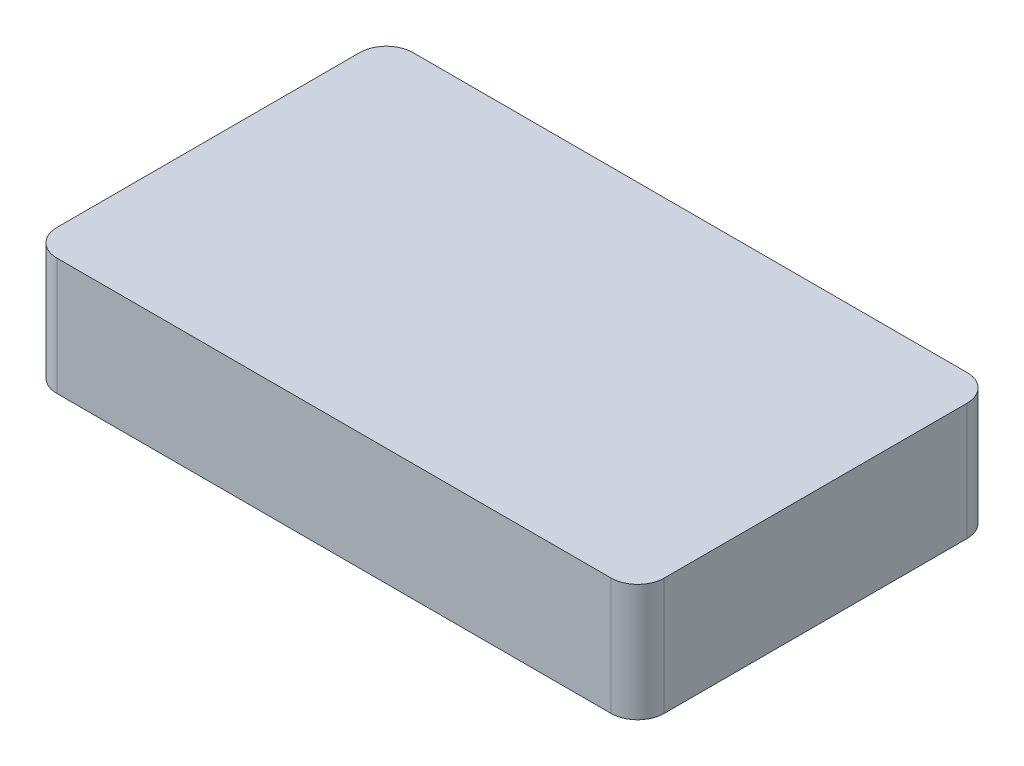
SolidWorks part; units mm, degrees
ref_plane "Front Plane" through (0, 0, 0) normal (0, 0, 1) x (1, 0, 0)
ref_plane "Top Plane" through (0, 0, 0) normal (0, 1, 0) x (1, 0, 0)
ref_plane "Right Plane" through (0, 0, 0) normal (1, 0, 0) x (0, 0, -1)
sketch "Sketch1" plane through (0, 0, 0) normal (0, 1, 0) x (1, 0, 0)
  line L1 (-66.15, 42.5) -> (66.15, 42.5)
  line L2 (-72.5, 36.15) -> (-72.5, -36.15)
  line L3 (-66.15, -42.5) -> (66.15, -42.5)
  line L4 (72.5, 36.15) -> (72.5, -36.15)
  arc A0 (66.15, 42.5) -> (72.5, 36.15) centre (66.15, 36.15) cw
  arc A1 (66.15, -42.5) -> (72.5, -36.15) centre (66.15, -36.15) ccw
  arc A2 (-72.5, -36.15) -> (-66.15, -42.5) centre (-66.15, -36.15) ccw
  arc A3 (-66.15, 42.5) -> (-72.5, 36.15) centre (-66.15, 36.15) ccw
  point P7 (72.5, 42.5)
  point P12 (-72.5, -42.5)
  point P15 (-72.5, 42.5)
  dimension "D5" = 6.35
  dimension "D1" = 145
  dimension "D2" = 85
  dimension "D3" = 72.5
  dimension "D4" = 42.5
extrude "Boss-Extrude1" add sketch "Sketch1" along normal blind 28
